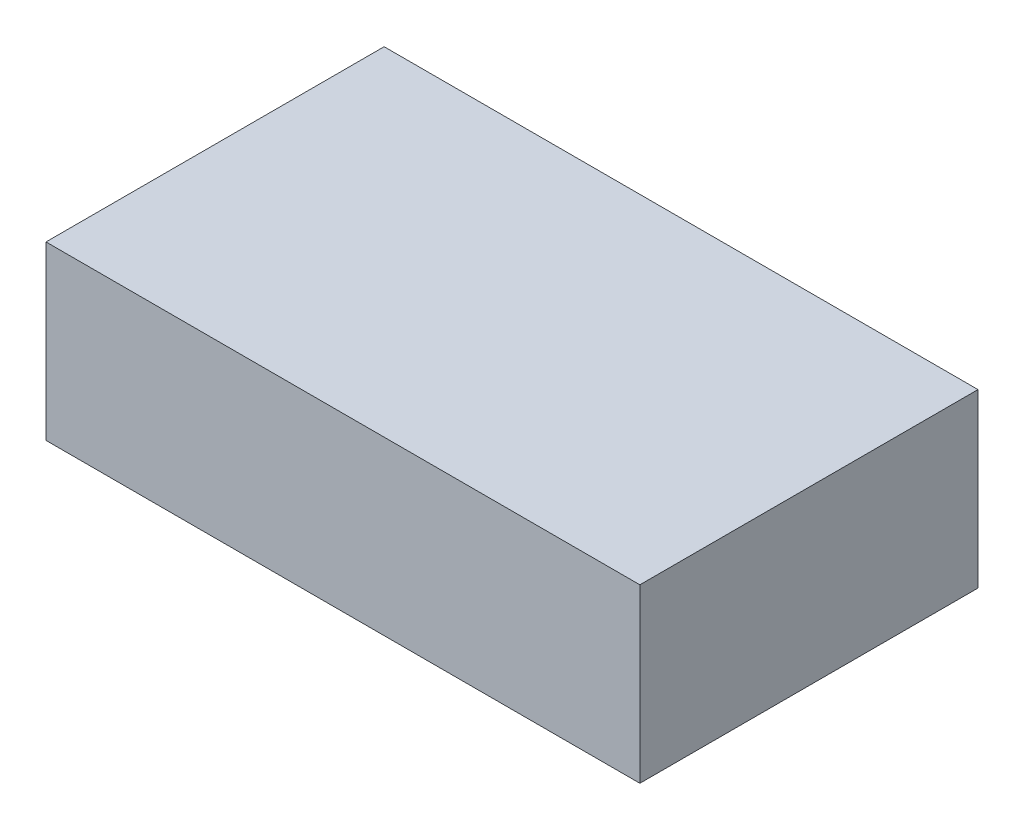
SolidWorks part; units mm, degrees
ref_plane "Front Plane" through (0, 0, 0) normal (0, 0, 1) x (1, 0, 0)
ref_plane "Top Plane" through (0, 0, 0) normal (0, 1, 0) x (1, 0, 0)
ref_plane "Right Plane" through (0, 0, 0) normal (1, 0, 0) x (0, 0, -1)
sketch "Sketch1" plane through (0, 0, 0) normal (0, 1, 0) x (1, 0, 0)
  line L1 (-52.25, 29.75) -> (52.25, 29.75)
  line L2 (-52.25, 29.75) -> (-52.25, -29.75)
  line L3 (-52.25, -29.75) -> (52.25, -29.75)
  line L4 (52.25, 29.75) -> (52.25, -29.75)
  line L5 (-52.25, 29.75) -> (52.25, -29.75) construction
  line L6 (-52.25, -29.75) -> (52.25, 29.75) construction
  point P0 (0, 0)
  dimension "D1" = 59.5
  dimension "D2" = 104.5
extrude "Boss-Extrude1" add sketch "Sketch1" along normal blind 30.25
sketch "Sketch2" plane through (-52.25, 0, 0) normal (-1, 0, 0) x (0, 0, 1)
  line L0 (0, 9.6) -> (0, 0) construction
  circle A0 centre (0, 11.6) radius 2
  dimension "D1" = 4
  dimension "D2" = 9.6
extrude "Boss-Extrude2" add sketch "Sketch2" along normal blind 10
sketch "Sketch5" plane through (0, 0, 0) normal (0, -1, 0) x (-1, 0, 0)
  line L4 (-36.5, 20.5) -> (36.5, 20.5) construction
  line L5 (36.5, 20.5) -> (36.5, -20.5) construction
  line L6 (36.5, -20.5) -> (-36.5, -20.5) construction
  line L7 (-36.5, -20.5) -> (-36.5, 20.5) construction
  point P41 (0, 20.5)
  point P43 (-36.5, 0)
  point P46 (-36.5, 20.5)
  point P49 (-36.5, -20.5)
  point P52 (36.5, -20.5)
  point P55 (36.5, 20.5)
  dimension "D1" = 41
  dimension "D2" = 73
hole_wizard "M4 Clearance Hole1" positions "Sketch5" profile "Sketch4" hole size "M4" standard "ANSI Metric"
sketch "Sketch4" plane through (-36.5, 0, -20.5) normal (1, 0, 0) x (0, 0, -1)
  line L0 (0, 0) -> (0, 11.3519)
  line L1 (0, 11.3519) -> (2.25, 10)
  line L2 (2.25, 10) -> (2.25, 0.025)
  line L3 (2.25, 0.025) -> (2.275, 0)
  line L5 (2.275, 0) -> (0, 0)
  line L6 (-2.25, 0.025) -> (-2.275, 0) construction
  line L10 (0, 11.3519) -> (-2.25, 10) construction
  line L11 (0, -6.35) -> (0, 107.95) construction
  dimension "Hole Dia." = 4.5
  dimension "Hole Depth" = 10
  dimension "Near C'Sink Dia." = 4.55
  dimension "Near C'Sink Angle" = 90
  dimension "Drill Angle" = 118
